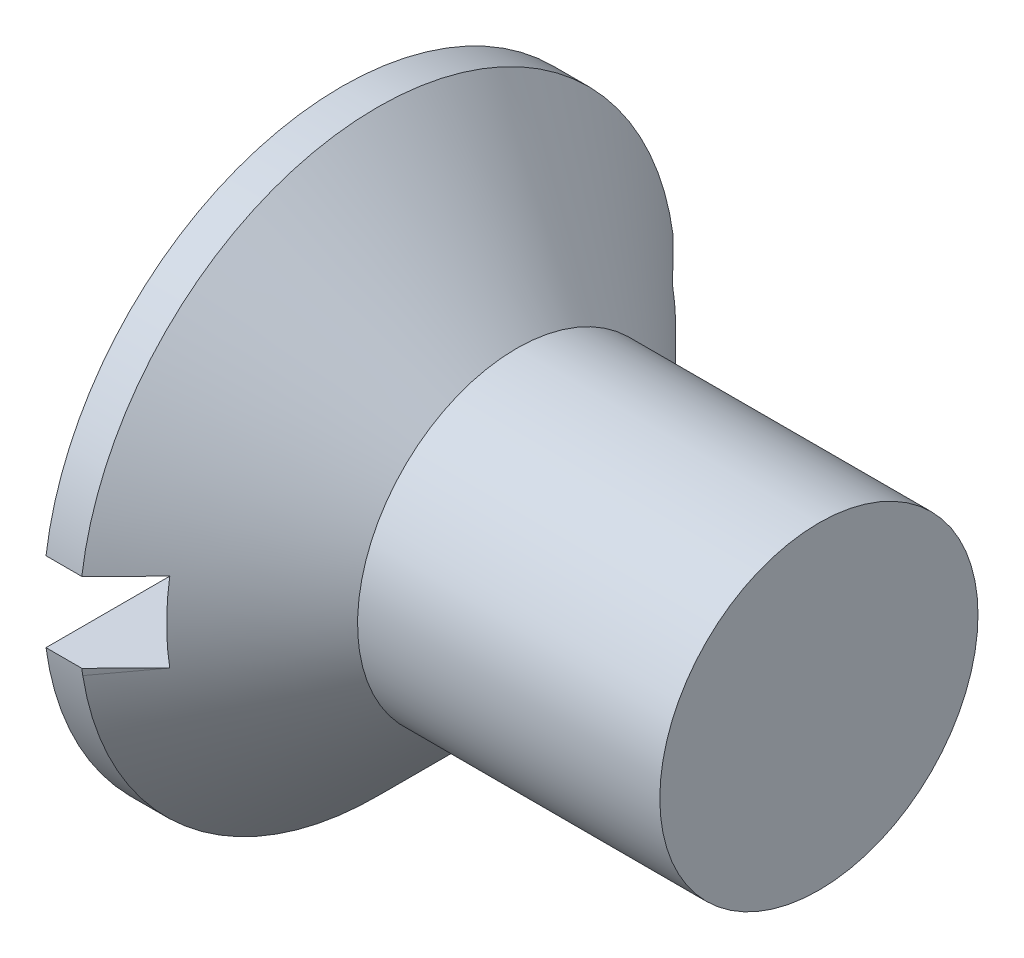
SolidWorks part; units mm, degrees
material "Plain Carbon Steel"
ref_plane "Front Plane" through (0, 0, 0) normal (0, 0, 1) x (1, 0, 0)
ref_plane "Top Plane" through (0, 0, 0) normal (0, 1, 0) x (1, 0, 0)
ref_plane "Right Plane" through (0, 0, 0) normal (1, 0, 0) x (0, 0, -1)
sketch "Sketch1" plane through (0, 0, 0) normal (0, 0, 1) x (1, 0, 0)
  line L0 (0, 0) -> (0, 3.75)
  line L1 (0, 3.75) -> (0.45, 3.75)
  line L2 (0.45, 3.75) -> (2.2, 2)
  line L3 (2.2, 2) -> (6, 2)
  line L4 (6, 2) -> (6, 0)
  line L5 (6, 0) -> (0, 0) construction
  line L6 (0, 0) -> (6, 0)
  dimension "D1" = 45
  dimension "D2" = 4
  dimension "D3" = 7.5
  dimension "D4" = 2.2
  dimension "D5" = 6
revolve "Revolve1" add sketch "Sketch1" angle 360 about L5
sketch "Sketch2" plane through (0, 0, 0) normal (-1, 0, 0) x (0, 0, 1)
  line L0 (3.75, 0) -> (-3.75, 0) construction
  line L1 (-3.75, 0.5) -> (3.75, 0.5)
  line L2 (-3.75, 0.5) -> (-3.75, -0.5)
  line L3 (-3.75, -0.5) -> (3.75, -0.5)
  line L4 (3.75, 0.5) -> (3.75, -0.5)
  circle A0 centre (0, 0) radius 3.75 construction
  dimension "D1" = 1
extrude "Cut-Extrude1" cut sketch "Sketch2" against normal blind 1
